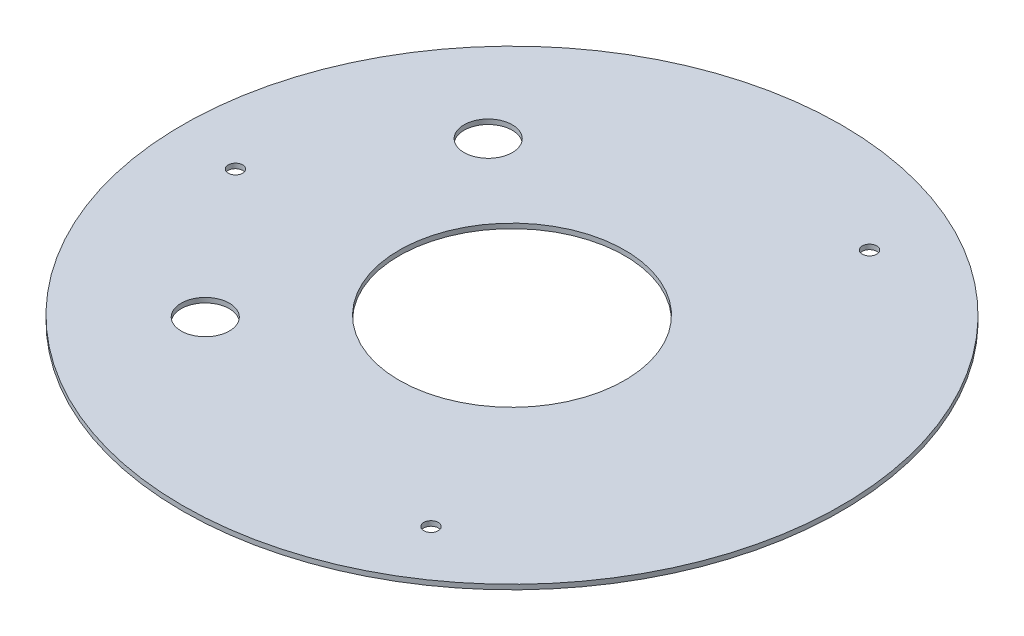
SolidWorks part; units mm, degrees
material "6061 Alloy"
ref_plane "Front Plane" through (0, 0, 0) normal (0, 0, 1) x (1, 0, 0)
ref_plane "Top Plane" through (0, 0, 0) normal (0, 1, 0) x (1, 0, 0)
ref_plane "Right Plane" through (0, 0, 0) normal (1, 0, 0) x (0, 0, -1)
sketch "Sketch1" plane through (0, 0, 0) normal (0, 1, 0) x (-1, 0, 0)
  circle A0 centre (-73.2496, 33.2167) radius 23.401
  circle A1 centre (-73.2496, 33.2167) radius 68.37
extrude "Boss-Extrude1" add sketch "Sketch1" along normal blind 1
sketch "Sketch2" plane through (0, 1, 0) normal (0, -1, 0) x (1, 0, 0)
  circle A0 centre (18.3031, 35.6411) radius 1.5
  circle A1 centre (102.8225, 79.5895) radius 1.5
  circle A2 centre (98.6233, -15.5807) radius 1.5
extrude "Cut-Extrude1" cut sketch "Sketch2" along normal blind 10
sketch "Sketch3" plane through (0, 1, 0) normal (0, 1, 0) x (-1, 0, 0)
  line L0 (-116.9404, -20.8125) -> (-123.2105, -15.0736)
  line L1 (-29.5305, 87.2199) -> (-23.3879, 81.5977)
  line L2 (-26.6402, 84.5744) -> (-120.1073, -17.9139) construction
sketch "Sketch5" plane through (0, 0, 0) normal (0, -1, 0) x (1, 0, 0)
  line L0 (26.9892, 84.1916) -> (120.1073, -17.9139)
  line L1 (26.6402, 84.5744) -> (120.1073, -17.9139) construction
extrude "Cut-Extrude2" cut sketch "Sketch6" against normal blind 10
sketch "Sketch6" plane through (47.342, -4, 109.3589) normal (0, -1, 0) x (0.0976, 0, 0.9952)
  circle A0 centre (-105.7022, -2.0425) radius 5
  circle A1 centre (-44.3242, 1.2553) radius 5
